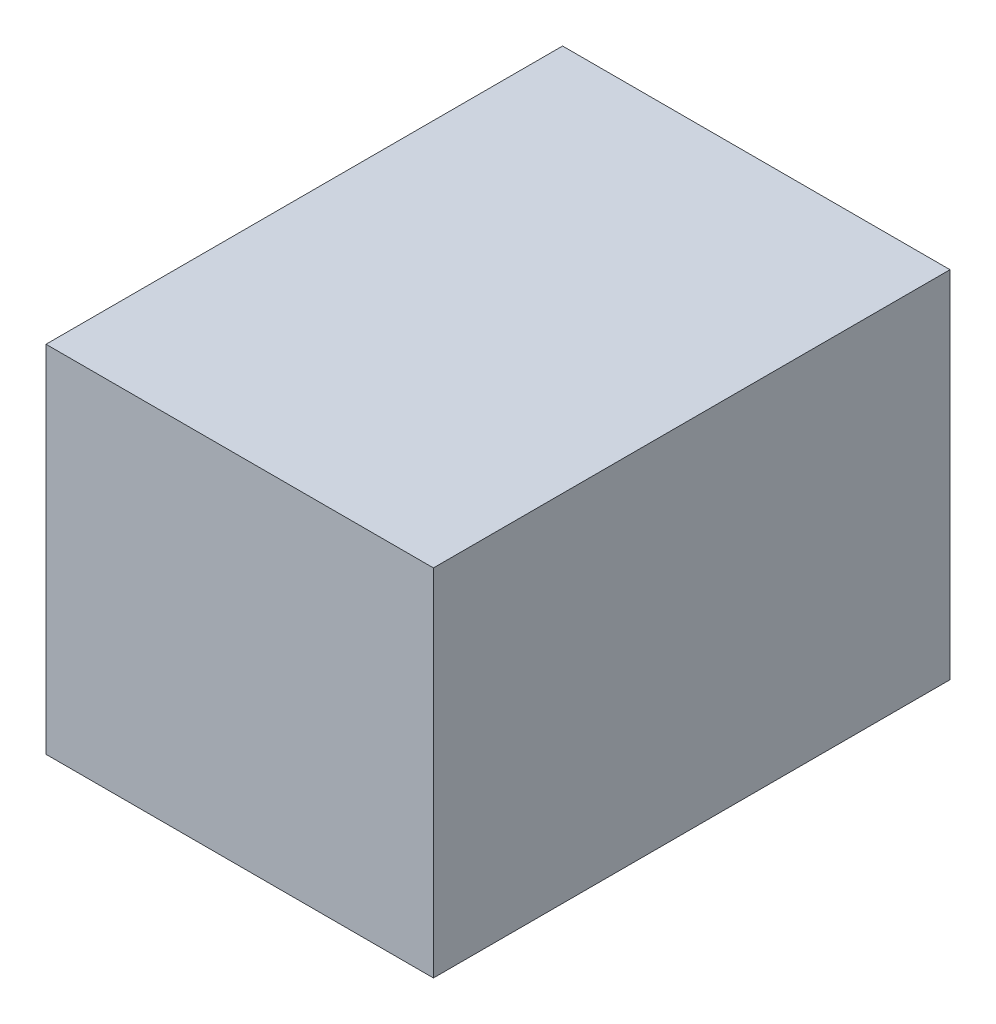
SolidWorks part; units mm, degrees
ref_plane "Front Plane" through (0, 0, 0) normal (0, 0, 1) x (1, 0, 0)
ref_plane "Top Plane" through (0, 0, 0) normal (0, 1, 0) x (1, 0, 0)
ref_plane "Right Plane" through (0, 0, 0) normal (1, 0, 0) x (0, 0, -1)
sketch "Sketch1" plane through (0, 0, 0) normal (0, 1, 0) x (1, 0, 0)
  line L1 (0, 0) -> (6, 0)
  line L2 (0, 0) -> (0, 8)
  line L3 (0, 8) -> (6, 8)
  line L4 (6, 0) -> (6, 8)
  dimension "D1" = 6
  dimension "D2" = 8
extrude "Boss-Extrude1" add sketch "Sketch1" along normal blind 5.5
